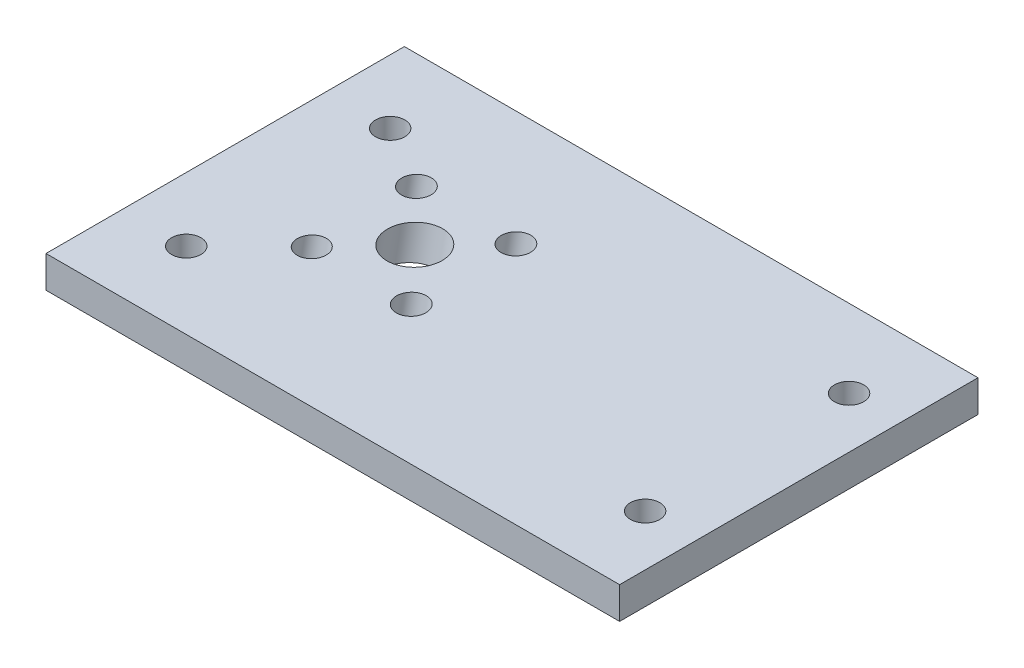
SolidWorks part; units mm, degrees
ref_plane "Front" through (0, 0, 0) normal (0, 0, 1) x (1, 0, 0)
ref_plane "Top" through (0, 0, 0) normal (0, 1, 0) x (1, 0, 0)
ref_plane "Right" through (0, 0, 0) normal (1, 0, 0) x (0, 0, -1)
sketch "Sketch1" plane through (0, 0, 0) normal (0, 1, 0) x (1, 0, 0)
  line L1 (0, 0) -> (90, 0)
  line L2 (0, 0) -> (0, 56.23)
  line L3 (0, 56.23) -> (90, 56.23)
  line L4 (90, 0) -> (90, 56.23)
  dimension "D1" = 90
  dimension "D2" = 56.23
extrude "Boss-Extrude1" add sketch "Sketch1" along normal blind 5
sketch "Sketch2" plane through (0, 5, 0) normal (0, 1, 0) x (1, 0, 0)
  circle A0 centre (82, 12) radius 2.3
  circle A1 centre (10, 12) radius 2.3
extrude "Cut-Extrude1" cut sketch "Sketch2" against normal blind 15
sketch "Sketch4" plane through (0, 5, 0) normal (0, 1, 0) x (1, 0, 0)
  circle A0 centre (39.2121, 27.5705) radius 2.204
  circle A1 centre (23.8176, 32.2728) radius 4.0674
  circle A2 centre (43.572, 44.174) radius 17.6111
  circle A3 centre (28.1775, 48.8763) radius 2.2
ref_plane "Plane1" through (0, 15.35, -2.9837) normal (0, 0.9816, -0.1908) x (-1, 0, 0)
sketch "Sketch7" plane through (0, 5, 0) normal (0, 1, 0) x (1, 0, 0)
  circle A0 centre (82, 44) radius 2.3
  circle A1 centre (10, 44) radius 2.3
extrude "Cut-Extrude3" cut sketch "Sketch7" against normal blind 45
sketch "Sketch8" plane through (0, 5, 0) normal (0, 1, 0) x (1, 0, 0)
  circle A0 centre (35.6711, 34.0145) radius 2.2
  circle A1 centre (19.6912, 34.0145) radius 2.2
  circle A2 centre (19.6912, 50.492) radius 2.2
  circle A3 centre (35.6711, 50.492) radius 2.2
  circle A4 centre (19.6912, 34.0145) radius 2.2
  circle A5 centre (35.6711, 34.0145) radius 2.2
  circle A6 centre (35.6711, 50.492) radius 2.2
  circle A7 centre (19.6912, 50.492) radius 2.2
sketch "Sketch10" plane through (0, 15.35, -2.9837) normal (0, 0.9816, -0.1908) x (-1, 0, 0)
  circle A0 centre (-35.6711, -32.4355) radius 2.1596
  circle A1 centre (-19.6912, -32.4355) radius 2.1596
  circle A2 centre (-19.6912, -48.6102) radius 2.1596
  circle A3 centre (-35.6711, -48.6102) radius 2.2
sketch "Sketch11" plane through (0, 5, 0) normal (0, 1, 0) x (1, 0, 0)
  circle A0 centre (35.5598, 21.7514) radius 2.3
  circle A1 centre (19.9455, 21.7514) radius 2.3
  circle A2 centre (35.5598, 38.1678) radius 2.3
  circle A3 centre (19.9455, 38.1678) radius 2.3
  circle A4 centre (27.7526, 30.1125) radius 4.1
sketch "Sketch12" plane through (0, 15.35, -2.9837) normal (0, 0.9816, -0.1908) x (-1, 0, 0)
  circle A0 centre (-19.9455, -20.3977) radius 2.2577
  circle A1 centre (-35.5598, -20.3977) radius 2.3
  circle A2 centre (-35.5598, -36.5125) radius 2.3
  circle A3 centre (-19.9455, -36.5125) radius 2.3
  circle A4 centre (-27.7526, -28.6052) radius 4.2873
extrude "Cut-Extrude5" cut sketch "Sketch12" against normal blind 20
